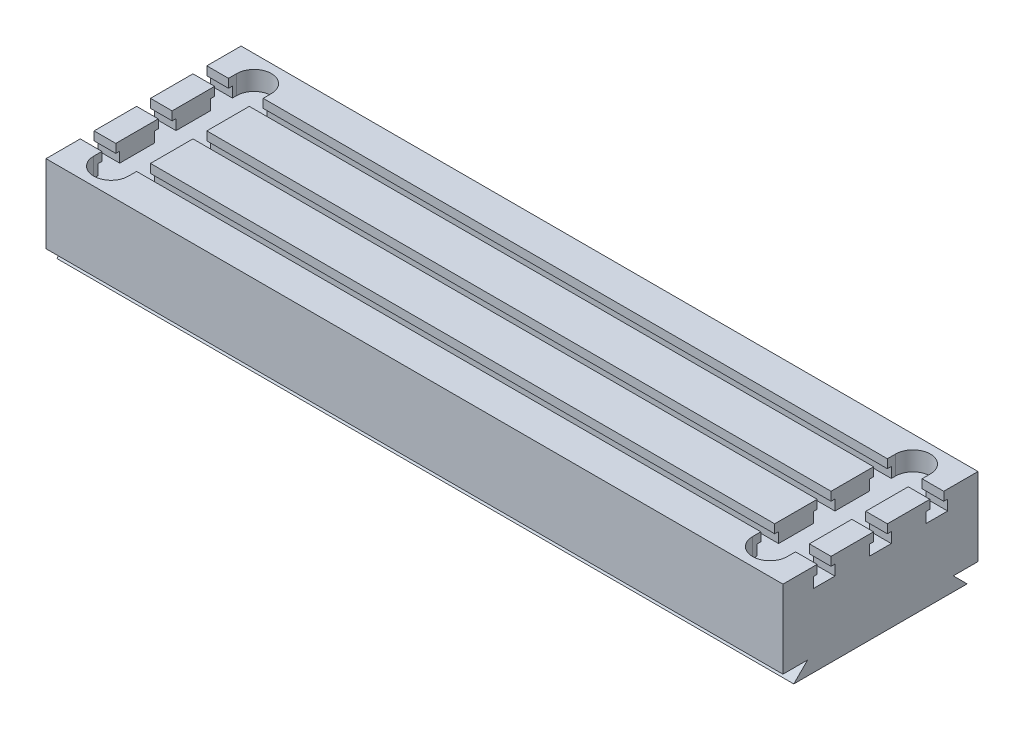
SolidWorks part; units mm, degrees
ref_plane "Front Plane" through (0, 0, 0) normal (0, 0, 1) x (1, 0, 0)
ref_plane "Top Plane" through (0, 0, 0) normal (0, 1, 0) x (1, 0, 0)
ref_plane "Right Plane" through (0, 0, 0) normal (1, 0, 0) x (0, 0, -1)
sketch "Sketch1" plane through (0, 0, 0) normal (0, 1, 0) x (1, 0, 0)
  line L1 (-850, 0) -> (0, 0)
  line L2 (-850, 0) -> (-850, -225)
  line L3 (-850, -225) -> (0, -225)
  line L4 (0, 0) -> (0, -225)
  point P4 (0, 0)
  dimension "D1" = 850
  dimension "D2" = 225
extrude "Boss-Extrude1" add sketch "Sketch1" along normal blind 106
sketch "Sketch2" plane through (0, 0, 0) normal (1, 0, 0) x (0, 0, -1)
  line L0 (-112.5, 0) -> (-112.5, 58.5979) construction
  line L4 (-225, 16) -> (-196.5, 16)
  line L5 (-225, 106) -> (-225, 0) construction
  line L7 (-225, 0) -> (-225, 16)
  line L8 (-225, 0) -> (0, 0) construction
  line L9 (-225, 0) -> (-212.5, 0)
  line L10 (-212.5, 0) -> (-196.5, 16)
  line L11 (0, 0) -> (-12.5, 0)
  line L12 (0, 0) -> (0, 16)
  line L13 (0, 16) -> (-28.5, 16)
  line L14 (-12.5, 0) -> (-28.5, 16)
  dimension "D1" = 112.5
  dimension "D2" = 16
  dimension "D3" = 45
  dimension "D4" = 200
extrude "Cut-Extrude1" cut sketch "Sketch2" against normal blind 850
sketch "Sketch3" plane through (0, 0, 0) normal (1, 0, 0) x (0, 0, -1)
  line L0 (-112.5, 0) -> (-112.5, 67.3305) construction
  line L1 (-120.5, 106) -> (-104.5, 106)
  line L2 (-55.5, 106) -> (-39.5, 106)
  line L3 (-39.5, 96) -> (-39.5, 106)
  line L4 (-120.5, 106) -> (-120.5, 96)
  line L5 (-225, 106) -> (0, 106) construction
  line L6 (-120.5, 96) -> (-125, 96)
  line L7 (-125, 96) -> (-125, 84)
  line L8 (-125, 84) -> (-100, 84)
  line L9 (-100, 84) -> (-100, 96)
  line L10 (-100, 96) -> (-104.5, 96)
  line L11 (-104.5, 96) -> (-104.5, 106)
  line L12 (-35, 96) -> (-39.5, 96)
  line L13 (-35, 84) -> (-35, 96)
  line L14 (-60, 84) -> (-35, 84)
  line L15 (-60, 96) -> (-60, 84)
  line L16 (-55.5, 96) -> (-60, 96)
  line L17 (-55.5, 106) -> (-55.5, 96)
  line L18 (-185.5, 106) -> (-169.5, 106)
  line L19 (-169.5, 96) -> (-169.5, 106)
  line L20 (-165, 96) -> (-169.5, 96)
  line L21 (-165, 84) -> (-165, 96)
  line L22 (-190, 84) -> (-165, 84)
  line L23 (-190, 96) -> (-190, 84)
  line L24 (-185.5, 96) -> (-190, 96)
  line L25 (-185.5, 106) -> (-185.5, 96)
  point P22 (0, 0)
  line M23 (0, 106) -> (-225, 106)
  dimension "D1" = 112.5
  dimension "D2" = 16
  dimension "D3" = 25
  dimension "D4" = 10
  dimension "D5" = 10
  dimension "D6" = 12
  dimension "D7" = 2
  dimension "D9" = 65
  dimension "D10" = 65
  dimension "D8" = 2
extrude "Cut-Extrude2" cut sketch "Sketch3" against normal blind 850 contours L25 L24 L23 L22 L21 L20 L19 M23 | L8 L0 L1 L4 L6 L7 | L0 L8 L9 L10 L11 M23 | L17 L16 L15 L14 L13 L12 L3 M23
sketch "Sketch4" plane through (0, 106, 0) normal (0, 1, 0) x (1, 0, 0)
  line L0 (-45, -195) -> (-45, -30) construction
  line L1 (-65, -195) -> (-65, -30)
  line L2 (-25, -195) -> (-25, -30)
  line L3 (0, -225) -> (0, -185.5) construction
  line L4 (-425, 104.8956) -> (-425, -417.869) construction
  line L5 (-990.9054, -112.5) -> (171.3577, -112.5) construction
  line L6 (-805, -195) -> (-805, -30) construction
  line L7 (-785, -195) -> (-785, -30)
  line L8 (-825, -195) -> (-825, -30)
  arc A0 (-65, -195) -> (-25, -195) centre (-45, -195) ccw
  arc A1 (-25, -30) -> (-65, -30) centre (-45, -30) ccw
  arc A2 (-785, -195) -> (-825, -195) centre (-805, -195) cw
  arc A3 (-825, -30) -> (-785, -30) centre (-805, -30) cw
  point P2 (-45, -112.5)
  point P14 (0, 0)
  point P18 (-805, -112.5)
  line M7 (0, -185.5) -> (-850, -185.5)
  dimension "D1" = 45
  dimension "D2" = 425
  dimension "D3" = 165
  dimension "D4" = 40
  dimension "D5" = 112.5
extrude "Cut-Extrude3" cut sketch "Sketch4" against normal blind 22 contours A3 L8 L7 M7 | A2 L7 L8 M7 | L1 A0 L2 M7 | L2 A1 L1 M7
